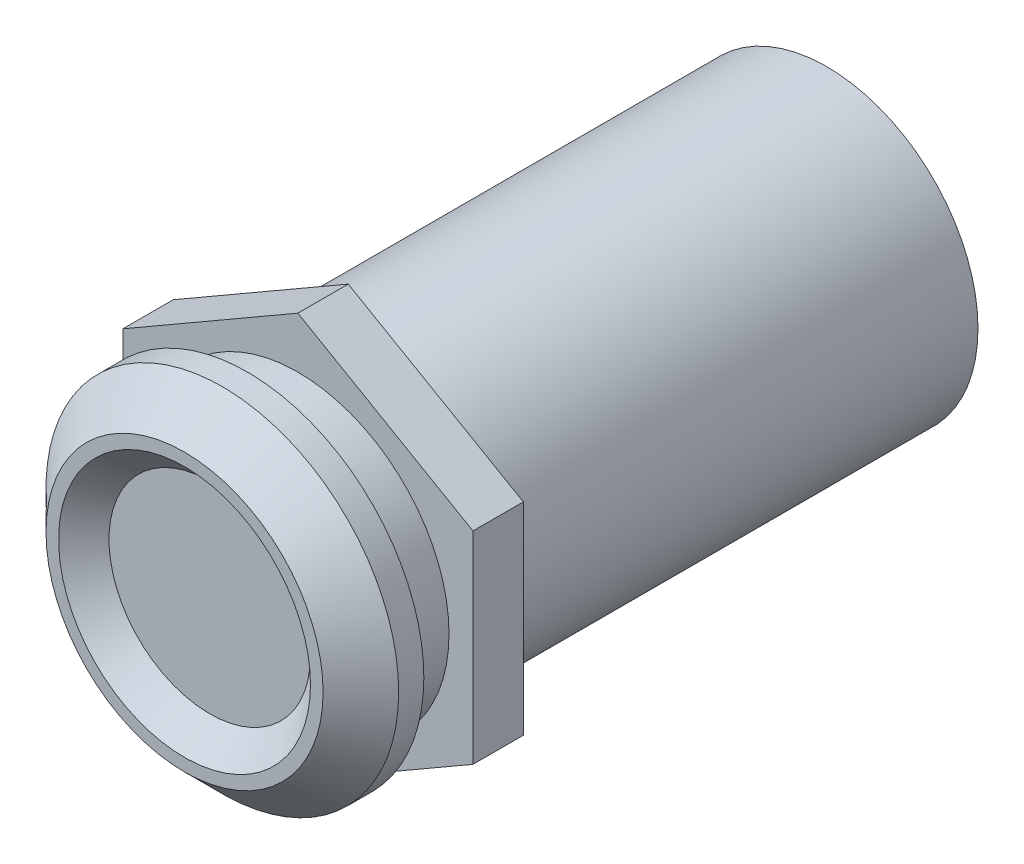
SolidWorks part; units mm, degrees
ref_plane "Front" through (0, 0, 0) normal (0, 0, 1) x (1, 0, 0)
ref_plane "Top" through (0, 0, 0) normal (0, 1, 0) x (1, 0, 0)
ref_plane "Right" through (0, 0, 0) normal (1, 0, 0) x (0, 0, -1)
sketch "Sketch1" plane through (0, 0, 0) normal (0, 0, 1) x (1, 0, 0)
  circle A0 centre (0, 0) radius 7
  dimension "D1" = 14
extrude "Boss-Extrude1" add sketch "Sketch1" along normal blind 1
sketch "Sketch2" plane through (0, 0, 1) normal (0, 0, 1) x (1, 0, 0)
  circle A1 centre (0, 0) radius 7
  circle A2 centre (0, 0) radius 7
  dimension "D1" = 0
extrude "Boss-Extrude2" add sketch "Sketch2" along normal blind 1.5 draft 45
sketch "Sketch3" plane through (0, 0, 2.5) normal (0, 0, 1) x (1, 0, 0)
  circle A2 centre (0, 0) radius 5
  circle A3 centre (0, 0) radius 5
  dimension "D1" = 0.5
extrude "Cut-Extrude1" cut sketch "Sketch3" against normal blind 1 draft 45
sketch "Sketch4" plane through (0, 0, 0) normal (0, 0, 1) x (1, 0, 0)
  circle A0 centre (0, 0) radius 6
  dimension "D1" = 12
extrude "Boss-Extrude3" add sketch "Sketch4" against normal blind 23
ref_plane "Plane1" through (0, 0, -2) normal (0, 0, 1) x (1, 0, 0)
sketch "Sketch5" plane through (0, 0, -2) normal (0, 0, 1) x (1, 0, 0)
  line L1 (0, 8.0252) -> (-6.95, 4.0126)
  line L2 (-6.95, 4.0126) -> (-6.95, -4.0126)
  line L3 (-6.95, -4.0126) -> (0, -8.0252)
  line L4 (0, -8.0252) -> (6.95, -4.0126)
  line L5 (6.95, -4.0126) -> (6.95, 4.0126)
  line L6 (6.95, 4.0126) -> (0, 8.0252)
  circle A0 centre (0, 0) radius 6.95 construction
  dimension "D1" = 13.9
extrude "Nut" add sketch "Sketch5" against normal blind 2
sketch "Panel Cut Guide" plane through (0, 0, 0) normal (0, 0, 1) x (1, 0, 0)
  circle A0 centre (0, 0) radius 6
  dimension "D1" = 12
